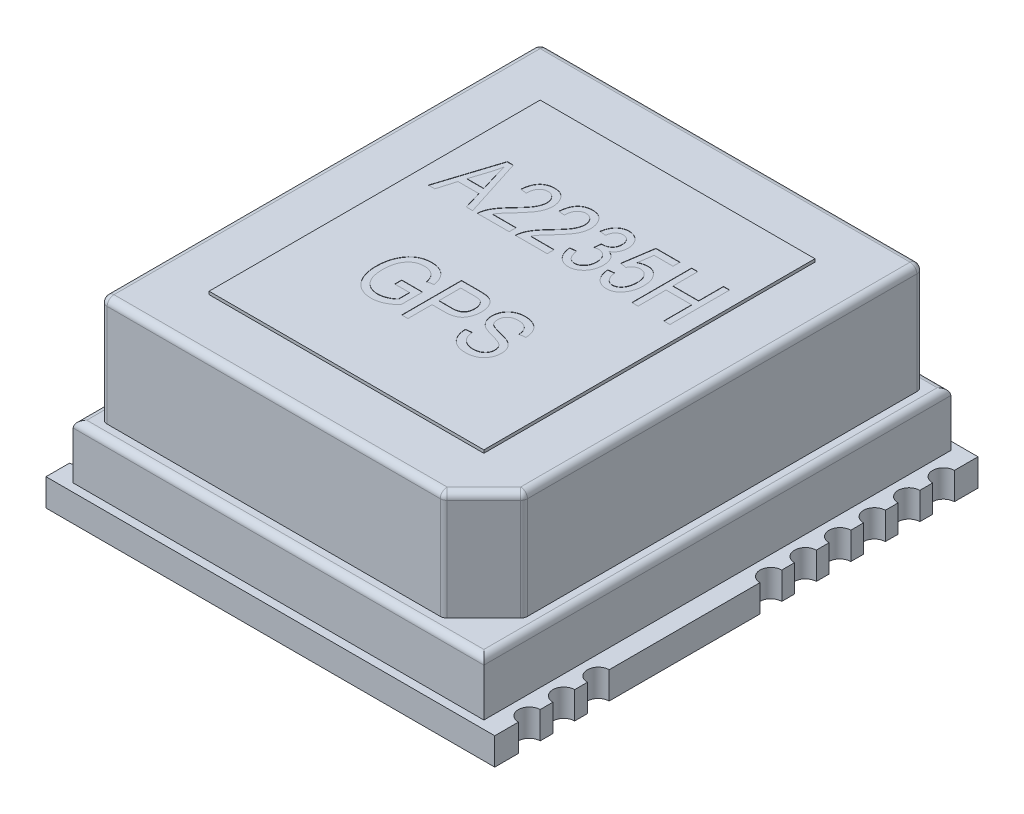
SolidWorks part; units mm, degrees
ref_plane "Front Plane" through (0, 0, 0) normal (0, 0, 1) x (1, 0, 0)
ref_plane "Top Plane" through (0, 0, 0) normal (0, 1, 0) x (1, 0, 0)
ref_plane "Right Plane" through (0, 0, 0) normal (1, 0, 0) x (0, 0, -1)
sketch "Sketch1" plane through (0, 0, 0) normal (0, 1, 0) x (1, 0, 0)
  line L1 (8.255, 8.89) -> (-8.255, 8.89)
  line L2 (8.255, 8.89) -> (8.255, -8.89)
  line L3 (8.255, -8.89) -> (-8.255, -8.89)
  line L4 (-8.255, 8.89) -> (-8.255, -8.89)
  line L5 (8.255, 8.89) -> (-8.255, -8.89) construction
  line L6 (8.255, -8.89) -> (-8.255, 8.89) construction
  dimension "D1" = 16.51
  dimension "D2" = 17.78
extrude "Boss-Extrude1" add sketch "Sketch1" along normal blind 1
sketch "Sketch2" plane through (0, 1, 0) normal (0, 1, 0) x (1, 0, 0)
  line L0 (0, 8.89) -> (0, -8.89) construction
  line L1 (-8.255, 8.89) -> (8.255, 8.89)
  line L2 (-8.255, 8.89) -> (-8.255, -8.89)
  line L3 (-8.255, -8.89) -> (8.255, -8.89)
  line L4 (8.255, 8.89) -> (8.255, -8.89)
  circle A0 centre (8.255, -7.62) radius 0.4
  circle A1 centre (-8.255, -7.62) radius 0.4
  circle A2 centre (-8.255, -6.35) radius 0.4
  circle A3 centre (8.255, -6.35) radius 0.4
  circle A4 centre (-8.255, -5.08) radius 0.4
  circle A5 centre (8.255, -5.08) radius 0.4
  circle A6 centre (-8.255, -3.81) radius 0.4
  circle A8 centre (-8.255, -2.54) radius 0.4
  circle A10 centre (-8.255, -1.27) radius 0.4
  circle A12 centre (-8.255, 0) radius 0.4
  circle A14 centre (-8.255, 1.27) radius 0.4
  circle A15 centre (8.255, 1.27) radius 0.4
  circle A16 centre (-8.255, 2.54) radius 0.4
  circle A17 centre (8.255, 2.54) radius 0.4
  circle A18 centre (-8.255, 3.81) radius 0.4
  circle A19 centre (8.255, 3.81) radius 0.4
  circle A20 centre (-8.255, 5.08) radius 0.4
  circle A21 centre (8.255, 5.08) radius 0.4
  circle A22 centre (-8.255, 6.35) radius 0.4
  circle A23 centre (8.255, 6.35) radius 0.4
  circle A24 centre (-8.255, 7.62) radius 0.4
  circle A25 centre (8.255, 7.62) radius 0.4
  circle A26 centre (8.255, -3.81) radius 0.4 [skipped]
  circle A27 centre (8.255, -2.54) radius 0.4 [skipped]
  circle A28 centre (8.255, -1.27) radius 0.4 [skipped]
  circle A29 centre (8.255, 0) radius 0.4 [skipped]
  dimension "D1" = 0.8
  dimension "D2" = 1.27
  dimension "D4" = 1.27
  dimension "D3" = 13
extrude "Cut-Extrude1" cut sketch "Sketch2" against normal up to next (1 mm away) contours A24 L2 | A24 L2 | A22 L2 | A22 L2 | A20 L2 | A20 L2 | A18 L2 | A18 L2 | A16 L2 | A16 L2 | A14 L2 | A14 L2 | A12 L2 | A12 L2 | A10 L2 | A10 L2 | A8 L2 | A8 L2 | A6 L2 | A6 L2 | A4 L2 | A4 L2 | A2 L2 | A2 L2 | A1 L2 | A1 L2 | L4 A25 | L4 A25 | L4 A23 | L4 A23 | L4 A21 | L4 A21 | L4 A19 | L4 A19 | L4 A17 | L4 A17 | L4 A15 | L4 A15 | L4 A5 | L4 A5 | L4 A3 | L4 A3 | L4 A0 | L4 A0
sketch "Sketch3" plane through (0, 1, 0) normal (0, 1, 0) x (1, 0, 0)
  line L0 (8.255, 8.89) -> (-8.255, 8.89) construction
  line L1 (-7.555, 8.59) -> (7.555, 8.59)
  line L2 (-7.555, 8.59) -> (-7.555, -8.59)
  line L3 (-7.555, -8.59) -> (7.555, -8.59)
  line L4 (7.555, 8.59) -> (7.555, -8.59)
  line L5 (-7.555, 8.59) -> (7.555, -8.59) construction
  line L6 (-7.555, -8.59) -> (7.555, 8.59) construction
  line L7 (8.255, 0.87) -> (8.255, -4.68) construction
  point P0 (0, 0)
  dimension "D1" = 0.3
  dimension "D2" = 0.7
extrude "Boss-Extrude2" add sketch "Sketch3" along normal blind 2
sketch "Sketch4" plane through (0, 3, 0) normal (0, 1, 0) x (1, 0, 0)
  line L0 (7.555, 8.59) -> (-7.555, 8.59) construction
  line L1 (7.055, 8.09) -> (-7.055, 8.09)
  line L2 (7.055, 8.09) -> (7.055, -6.59)
  line L3 (5.555, -8.09) -> (-7.055, -8.09)
  line L4 (-7.055, 8.09) -> (-7.055, -8.09)
  line L5 (7.055, 8.09) -> (-7.055, -8.09) construction
  line L6 (7.055, -8.09) -> (-7.055, 8.09) construction
  line L7 (-7.555, 8.59) -> (-7.555, -8.59) construction
  line L8 (7.055, -6.59) -> (5.555, -8.09)
  point P0 (0, 0)
  dimension "D1" = 0.5
  dimension "D2" = 0.5
extrude "Boss-Extrude3" add sketch "Sketch4" along normal blind 4
sketch "Sketch6" plane through (0, 7, 0) normal (0, 1, 0) x (1, 0, 0)
  line L0 (-7.055, -8.09) -> (5.555, -8.09) construction
  line L1 (5.055, 6.09) -> (-5.055, 6.09)
  line L2 (5.055, 6.09) -> (5.055, -6.09)
  line L3 (5.055, -6.09) -> (-5.055, -6.09)
  line L4 (-5.055, 6.09) -> (-5.055, -6.09)
  line L5 (5.055, 6.09) -> (-5.055, -6.09) construction
  line L6 (5.055, -6.09) -> (-5.055, 6.09) construction
  line L7 (-7.055, 8.09) -> (-7.055, -8.09) construction
  point P0 (0, 0)
  dimension "D1" = 2
  dimension "D2" = 2
extrude "Boss-Extrude4" add sketch "Sketch6" along normal blind 0.11
sketch "Sketch7" plane through (0, 7.11, 0) normal (0, 1, 0) x (1, 0, 0)
  line L0 (-4.4011, 1.3249) -> (3.8942, 1.3249) construction
  text T0 "A2235H\r\nGPS" font "Arial Narrow" height 2.2
extrude "Cut-Extrude2" cut sketch "Sketch7" against normal blind 0.01
fillet "Fillet1" radius 0.25 4 edges at (0, 3, -8.59) (7.555, 3, 0) (0, 3, 8.59) (-7.555, 3, 0)
fillet "Fillet2" radius 0.25 10 edges at (7.055, 5, 6.59) (5.555, 5, 8.09) (7.055, 5, -8.09) (-7.055, 5, 8.09) (-7.055, 5, -8.09) (0, 7, -8.09) (7.055, 7, -0.75) (6.305, 7, 7.34) (-0.75, 7, 8.09) (-7.055, 7, 0)
